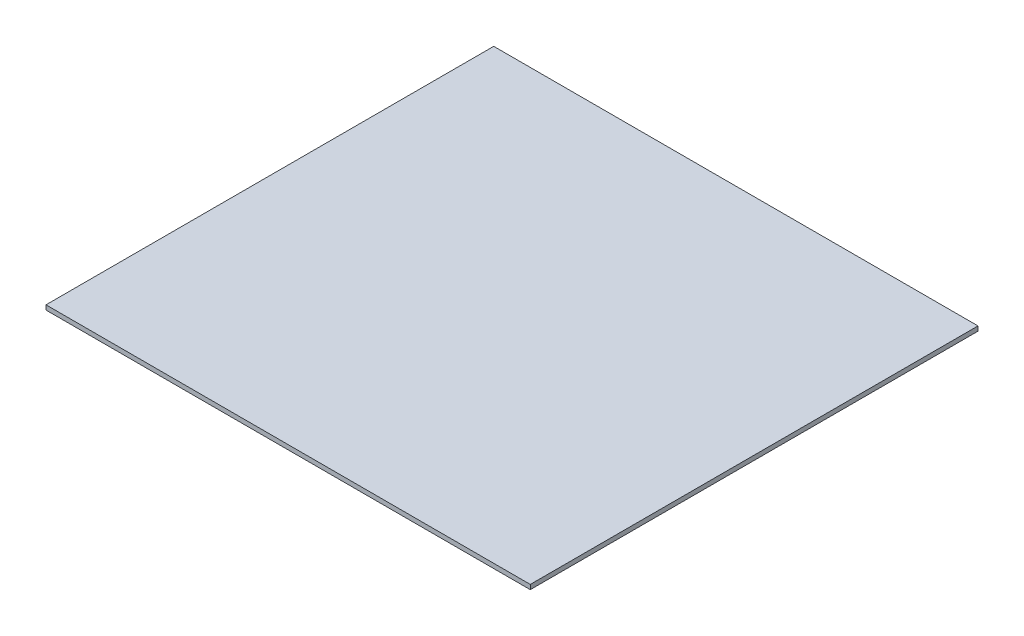
SolidWorks part; units mm, degrees
ref_plane "Front Plane" through (0, 0, 0) normal (0, 0, 1) x (1, 0, 0)
ref_plane "Top Plane" through (0, 0, 0) normal (0, 1, 0) x (1, 0, 0)
ref_plane "Right Plane" through (0, 0, 0) normal (1, 0, 0) x (0, 0, -1)
sketch "Sketch1" plane through (0, 0, 0) normal (0, 1, 0) x (1, 0, 0)
  line L1 (-53, 49) -> (53, 49)
  line L2 (-53, 49) -> (-53, -49)
  line L3 (-53, -49) -> (53, -49)
  line L4 (53, 49) -> (53, -49)
  point P4 (0, 49)
  point P6 (53, 0)
  dimension "D1" = 106
  dimension "D2" = 98
extrude "Boss-Extrude1" add sketch "Sketch1" along normal blind 1
